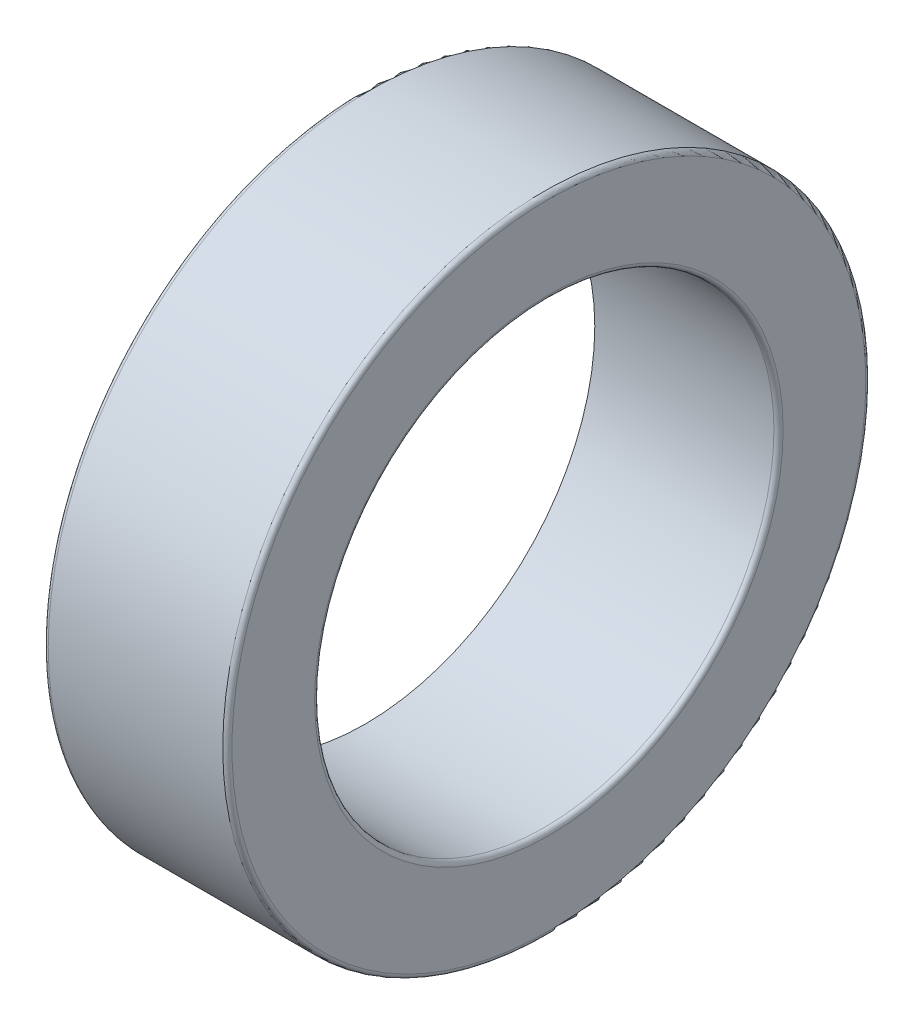
SolidWorks part; units mm, degrees
ref_plane "Front Plane" through (0, 0, 0) normal (0, 0, 1) x (1, 0, 0)
ref_plane "Top Plane" through (0, 0, 0) normal (0, 1, 0) x (1, 0, 0)
ref_plane "Right Plane" through (0, 0, 0) normal (1, 0, 0) x (0, 0, -1)
sketch "Sketch1" plane through (0, 0, 0) normal (1, 0, 0) x (0, 0, -1)
  circle A0 centre (0, 0) radius 88.9
  circle A1 centre (0, 0) radius 63.5
  dimension "D1" = 177.8
  dimension "D2" = 127
extrude "Boss-Extrude1" add sketch "Sketch1" along normal mid plane 50.8
fillet "Fillet1" radius 1.27 3 edges at (25.4, 0, -63.5) (25.4, 0, -88.9) (-25.4, 0, -88.9)
